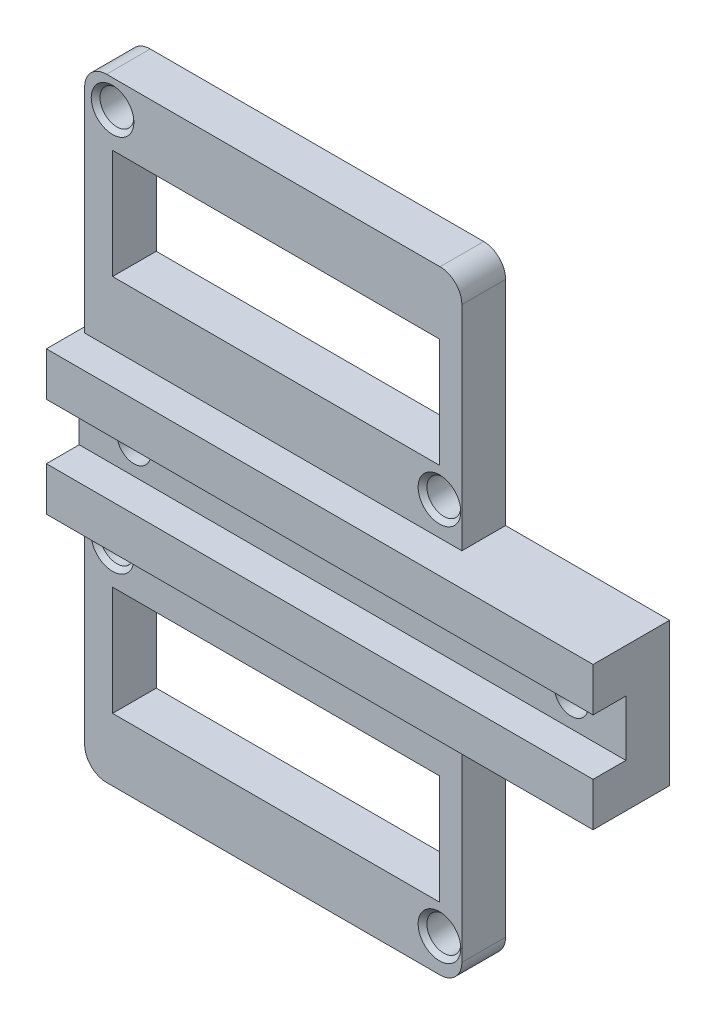
SolidWorks part; units mm, degrees
ref_plane "Alzado" through (0, 0, 0) normal (0, 0, 1) x (1, 0, 0)
ref_plane "Planta" through (0, 0, 0) normal (0, 1, 0) x (1, 0, 0)
ref_plane "Vista lateral" through (0, 0, 0) normal (1, 0, 0) x (0, 0, -1)
sketch "Croquis1" plane through (0, 0, 0) normal (0, 0, 1) x (1, 0, 0)
  line L0 (-20, 0) -> (20, 0) construction
  line L1 (-20, 0) -> (20, 0) construction
  line L2 (-20, 2.55) -> (20, 2.55)
  line L3 (-20, -2.55) -> (20, -2.55)
  line L4 (-20, 2.55) -> (-25, 2.55)
  line L5 (-25, 2.55) -> (-25, -2.55)
  line L6 (-25, -2.55) -> (-20, -2.55)
  line L7 (20, 2.55) -> (25, 2.55)
  line L8 (25, 2.55) -> (25, -2.55)
  line L9 (25, -2.55) -> (20, -2.55)
  circle A0 centre (20, 0) radius 1.55
  circle A1 centre (-20, 0) radius 1.55
  arc A2 (-20, 2.55) -> (-20, -2.55) centre (-20, 0) ccw
  arc A3 (20, -2.55) -> (20, 2.55) centre (20, 0) ccw
  point P4 (0, 0)
  point P7 (0, 0)
  dimension "D2" = 3.1
  dimension "D1" = 40
  dimension "D3" = 5.1
  dimension "D4" = 5
  dimension "D5" = 5
extrude "Saliente-Extruir1" add sketch "Croquis1" along normal blind 4 contours A2 L4 L5 L6 | L3 A3 L2 A2 A1 A0 | A3 L9 L8 L7
sketch "Croquis2" plane through (0, 0, 0) normal (0, 0, 1) x (1, 0, 0)
  line L0 (25, 2.55) -> (-25, 2.55) construction
  line L1 (-25, 2.55) -> (25, 2.55)
  line L2 (-25, 2.55) -> (-25, 6.55)
  line L3 (-25, 6.55) -> (25, 6.55)
  line L4 (25, 2.55) -> (25, 6.55)
  line L6 (-25, -2.55) -> (25, -2.55)
  line L7 (-25, -2.55) -> (-25, -6.55)
  line L8 (-25, -6.55) -> (25, -6.55)
  line L9 (25, -2.55) -> (25, -6.55)
  dimension "D1" = 4
extrude "Saliente-Extruir2" add sketch "Croquis2" along normal blind 7
sketch "Croquis3" plane through (0, 0, 7) normal (0, 0, 1) x (1, 0, 0)
  line L0 (-21.95, 27.05) -> (-12.91, 27.05) construction
  line L1 (-29, 28.05) -> (14.5, 28.05)
  line L2 (-29, 28.05) -> (-29, 6.55)
  line L3 (-29, 6.55) -> (14.5, 6.55)
  line L4 (14.5, 28.05) -> (14.5, 6.55)
  line L5 (7.95, 8.05) -> (17.0979, 8.05) construction
  line L6 (-24.5, 28.05) -> (-24.5, 6.55)
  line L7 (10, 6.55) -> (10, 28.05)
  line L8 (25, 6.55) -> (-25, 6.55) construction
  line L9 (-21.95, 22.3) -> (7.95, 22.3)
  line L10 (-21.95, 22.3) -> (-21.95, 12.3)
  line L11 (-21.95, 12.3) -> (7.95, 12.3)
  line L12 (7.95, 22.3) -> (7.95, 12.3)
  line L13 (-20, 0) -> (20, 0) construction
  line L14 (-21.95, -7.55) -> (-51.3179, -7.55) construction
  line L15 (-29, -6.55) -> (14.5, -6.55)
  line L16 (-29, -6.55) -> (-29, -28.05)
  line L17 (14.5, -6.55) -> (14.5, -28.05)
  line L18 (-24.5, -6.55) -> (-24.5, -28.05)
  line L19 (10, -36.8886) -> (10, -6.55)
  line L20 (-21.95, -12.3) -> (7.95, -12.3)
  line L21 (-21.95, -12.3) -> (-21.95, -22.3)
  line L22 (-21.95, -22.3) -> (7.95, -22.3)
  line L23 (7.95, -12.3) -> (7.95, -22.3)
  line L24 (-29, -28.05) -> (14.5, -28.05)
  line L25 (7.95, -26.55) -> (-34.4129, -26.55) construction
  line L26 (10, -36.8886) -> (10, -28.05)
  line L27 (-25, -6.55) -> (25, -6.55) construction
  circle A0 centre (-21.95, 25.5) radius 1.55
  circle A1 centre (7.95, 9.6) radius 1.55
  circle A2 centre (-21.95, -9.1) radius 1.55
  circle A3 centre (7.95, -25) radius 1.55
  point P27 (-24.5, 17.3)
  point P28 (-21.95, 17.3)
  point P48 (-24.5, -17.3)
  point P49 (-21.95, -17.3)
  point P50 (-7, 12.3)
  dimension "D3" = 3.1
  dimension "D4" = 7.05
  dimension "D5" = 6.55
  dimension "D13" = 3.1
  dimension "D1" = 21.5
  dimension "D2" = 43.5
  dimension "D6" = 1
  dimension "D7" = 1.5
  dimension "D8" = 4.5
  dimension "D9" = 4.5
  dimension "D10" = 10
  dimension "D11" = 4.5
  dimension "D12" = 4.5
  dimension "D14" = 29.9
  dimension "D15" = 7.05
  dimension "D16" = 1
  dimension "D17" = 1.5
  dimension "D18" = 2.05
  dimension "D19" = 5.75
  dimension "D20" = 7
extrude "Saliente-Extruir3" add sketch "Croquis3" along normal blind 4 from surface at -7 contours L3 L7 L1 L6 A1 A0 L9 L12 L11 L10 | L18 L24 L19 L15 A3 A2 L20 L23 L22 L21 starting at face at (0, 0, 0)
fillet "Redondeo1" radius 2 4 edges at (-24.5, -28.05, 2) (10, -28.05, 2) (10, 28.05, 2) (-24.5, 28.05, 2)
chamfer "Chaflán1" distance 0.4 angle 45 4 edges at (9.5, -25, 4) (-20.4, -9.1, 4) (9.5, 9.6, 4) (-20.4, 25.5, 4)
